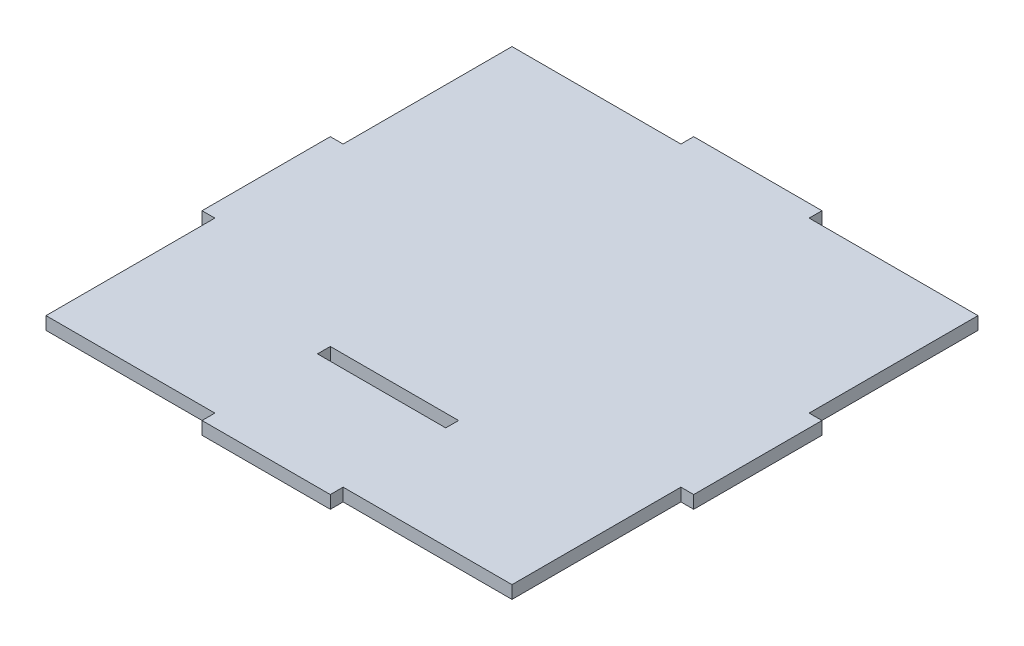
SolidWorks part; units mm, degrees
ref_plane "Front Plane" through (0, 0, 0) normal (0, 0, 1) x (1, 0, 0)
ref_plane "Top Plane" through (0, 0, 0) normal (0, 1, 0) x (1, 0, 0)
ref_plane "Right Plane" through (0, 0, 0) normal (1, 0, 0) x (0, 0, -1)
sketch "Sketch1" plane through (0, 0, 0) normal (0, 1, 0) x (1, 0, 0)
  line L0 (-57.5, 15) -> (-54.5, 15)
  line L1 (57.5, 57.5) -> (-57.5, 57.5)
  line L2 (57.5, 57.5) -> (57.5, -57.5)
  line L3 (57.5, -57.5) -> (-57.5, -57.5)
  line L4 (-57.5, 57.5) -> (-57.5, -57.5)
  line L5 (57.5, 57.5) -> (-57.5, -57.5) construction
  line L6 (57.5, -57.5) -> (-57.5, 57.5) construction
  line L7 (-54.5, 15) -> (-54.5, -15)
  line L8 (-54.5, -15) -> (-57.5, -15)
  line L9 (-15, 57.5) -> (-15, 54.5)
  line L10 (-15, 54.5) -> (15, 54.5)
  line L11 (15, 54.5) -> (15, 57.5)
  line L12 (57.5, 15) -> (54.5, 15)
  line L13 (54.5, 15) -> (54.5, -15)
  line L14 (54.5, -15) -> (57.5, -15)
  line L15 (-15, -57.5) -> (-15, -54.5)
  line L16 (-15, -54.5) -> (15, -54.5)
  line L17 (15, -54.5) -> (15, -57.5)
  line L18 (0, 57.5) -> (0, -57.5) construction
  line L19 (-57.5, 0) -> (57.5, 0) construction
  line L20 (0.2252, 54.5727) -> (0.2252, -60.4273) construction
  line L21 (-54.5, 15) -> (-54.5, 54.5)
  line L22 (-54.5, 54.5) -> (-15, 54.5)
  line L23 (15, 54.5) -> (54.5, 54.5)
  line L24 (54.5, 54.5) -> (54.5, 15)
  line L25 (54.5, -15) -> (54.5, -54.5)
  line L26 (54.5, -54.5) -> (15, -54.5)
  line L27 (-15, -54.5) -> (-54.5, -54.5)
  line L28 (-54.5, -54.5) -> (-54.5, -15)
  point P0 (0, 0)
  dimension "D1" = 115
  dimension "D2" = 115
  dimension "D3" = 3
  dimension "D4" = 30
extrude "Boss-Extrude1" add sketch "Sketch1" along normal blind 3 contours L17 L16 L15 L3 | L8 L7 L0 L4 | L10 L11 L1 L9 | L28 L27 L16 L26 L25 L13 L24 L23 L10 L22 L21 L7 | L13 L14 L2 L12
sketch "Sketch2" plane through (0, 3, 0) normal (0, 1, 0) x (1, 0, 0)
  line L0 (0, -57.5) -> (0, 57.5) construction
  line L1 (-15, -30.5) -> (15, -30.5)
  line L2 (-15, -30.5) -> (-15, -27.5)
  line L3 (-15, -27.5) -> (15, -27.5)
  line L4 (15, -30.5) -> (15, -27.5)
  line L5 (15, -57.5) -> (-15, -57.5) construction
  line L6 (15, 57.5) -> (-15, 57.5) construction
  point P10 (0, 0)
  dimension "D1" = 3
  dimension "D2" = 30
  dimension "D3" = 27
extrude "Cut-Extrude1" cut sketch "Sketch2" against normal blind 10
